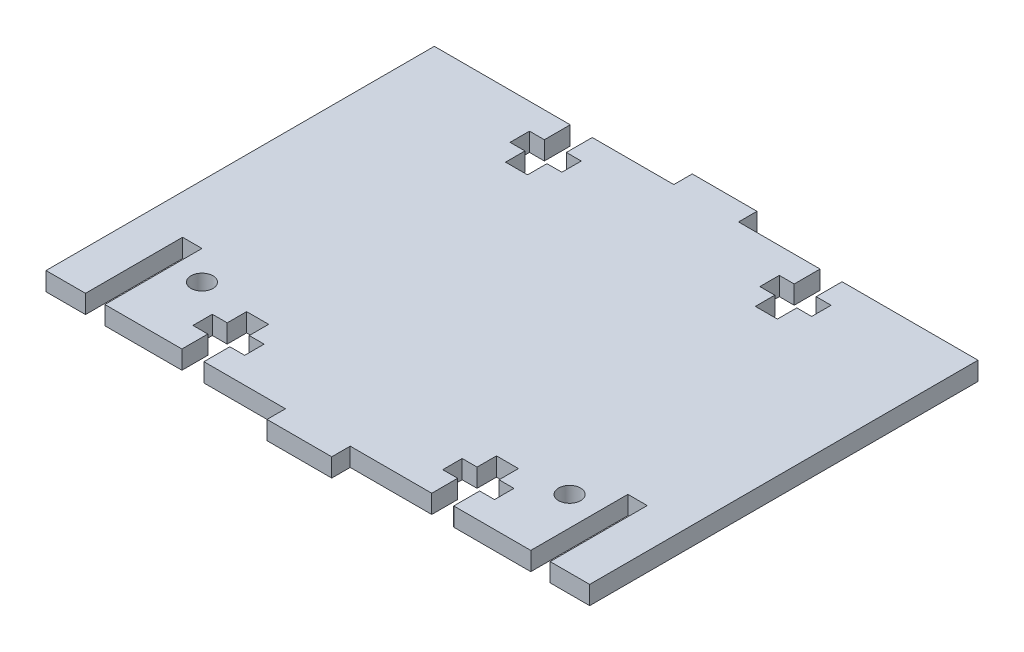
SolidWorks part; units mm, degrees
material "Pine"
ref_plane "Front" through (0, 0, 0) normal (0, 0, 1) x (1, 0, 0)
ref_plane "Top" through (0, 0, 0) normal (0, 1, 0) x (1, 0, 0)
ref_plane "Right" through (0, 0, 0) normal (1, 0, 0) x (0, 0, -1)
sketch "Sketch1" plane through (0, 0, 0) normal (0, 1, 0) x (1, 0, 0)
  line L1 (-42, 30) -> (42, 30)
  line L2 (-42, 30) -> (-42, -30)
  line L3 (-42, -30) -> (42, -30)
  line L4 (42, 30) -> (42, -30)
  line L5 (-42, 30) -> (42, -30) construction
  line L6 (-42, -30) -> (42, 30) construction
  point P0 (0, 0)
  dimension "D1" = 84
  dimension "D2" = 60
extrude "Boss-Extrude1" add sketch "Sketch1" along normal blind 2.85
sketch "Sketch2" plane through (0, 0, 0) normal (0, -1, 0) x (1, 0, 0)
  line L0 (-42, 30) -> (42, 30) construction
  line L1 (-32.9, 15) -> (-35.9, 15)
  line L2 (-32.9, 15) -> (-32.9, 30)
  line L3 (-32.9, 30) -> (-35.9, 30)
  line L4 (-35.9, 15) -> (-35.9, 30)
  line L5 (-42, -30) -> (-42, 30) construction
  dimension "D1" = 15
  dimension "D2" = 3
  dimension "D3" = 6.1
extrude "Cut-Extrude1" cut sketch "Sketch2" against normal through all
mirror "Mirror1" about plane through (0, 0, 0) normal (1, 0, 0) of "Cut-Extrude1"
sketch "Sketch3" plane through (0, 2.85, 0) normal (0, 1, 0) x (1, 0, 0)
  line L0 (42, 30) -> (-42, 30) construction
  line L1 (-23.3, 26) -> (-21, 26)
  line L2 (-23.3, 26) -> (-23.3, 23)
  line L3 (-23.3, 23) -> (-21, 23)
  line L4 (-15.3, 26) -> (-15.3, 23)
  line L5 (-42, 30) -> (-42, -30) construction
  line L7 (-21, 20) -> (-17.6, 20)
  line L8 (-21, 20) -> (-21, 23)
  line L9 (-21, 30) -> (-17.6, 30)
  line L10 (-17.6, 20) -> (-17.6, 23)
  line L16 (-21, 26) -> (-21, 30)
  line L19 (-17.6, 26) -> (-15.3, 26)
  line L20 (-17.6, 26) -> (-17.6, 30)
  line L22 (-17.6, 23) -> (-15.3, 23)
  point P5 (-27, 26)
  dimension "D1" = 3.4
  dimension "D2" = 3
  dimension "D3" = 8
  dimension "D4" = 10
  dimension "D5" = 21
  dimension "D6" = 3
extrude "Cut-Extrude2" cut sketch "Sketch3" against normal through all
mirror "Mirror2" about plane through (0, 0, 0) normal (1, 0, 0) of "Cut-Extrude2"
sketch "Sketch4" plane through (0, 2.85, 0) normal (0, 1, 0) x (1, 0, 0)
  line L0 (17.6, 30) -> (-17.6, 30) construction
  line L1 (-5, 30) -> (5, 30)
  line L2 (-5, 30) -> (-5, 32.85)
  line L3 (-5, 32.85) -> (5, 32.85)
  line L4 (5, 30) -> (5, 32.85)
  line L5 (0, 30) -> (0, 0) construction
  dimension "D1" = 2.85
  dimension "D2" = 10
extrude "Boss-Extrude2" add sketch "Sketch4" against normal blind 2.85
mirror "Mirror3" about plane through (0, 0, 0) normal (0, 0, 1) of "Mirror2", "Boss-Extrude2", "Cut-Extrude2"
extrude "Cut-Extrude3" cut sketch "Sketch5" against normal blind 6
sketch "Sketch5" plane through (0, 5.35, 32.85) normal (0, 1, 0) x (1, 0, 0)
  circle A0 centre (-28.4, 13.35) radius 1.7
mirror "Mirror4" about plane through (0, 0, 0) normal (1, 0, 0) of "Cut-Extrude3"
